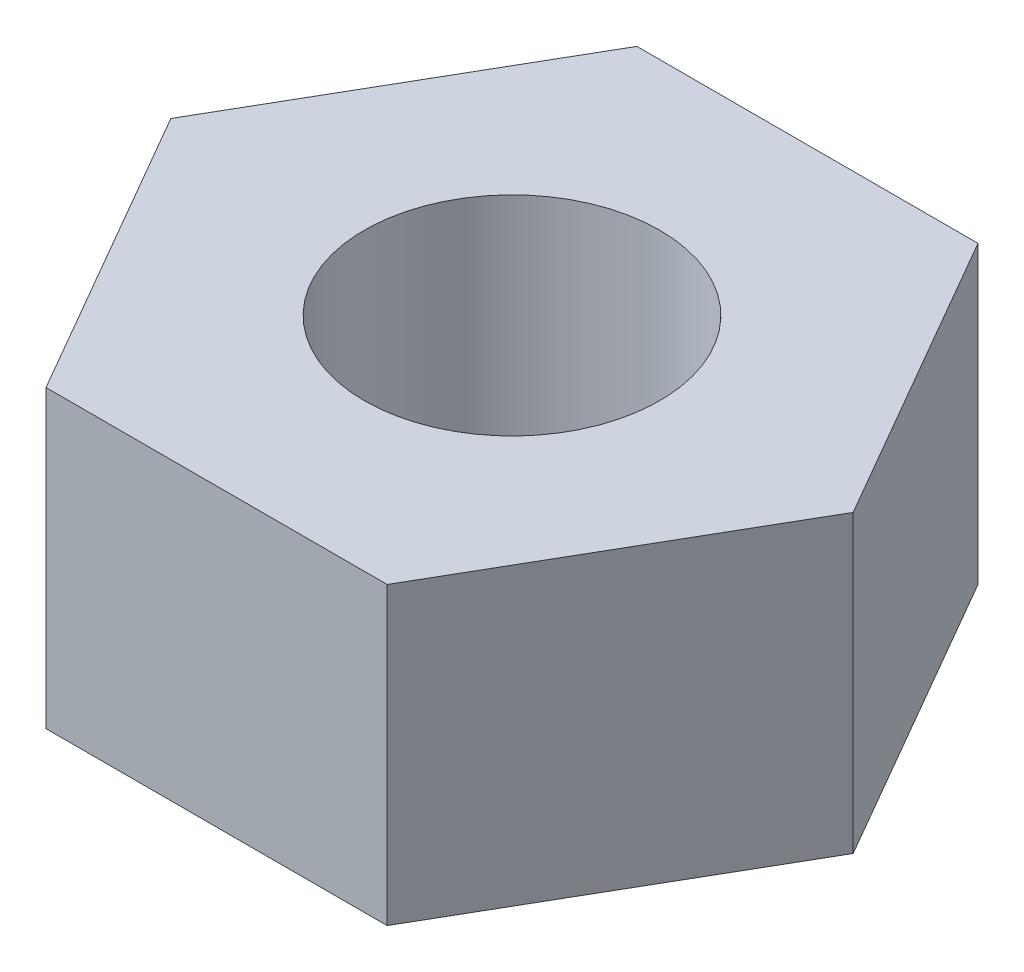
SolidWorks part; units mm, degrees
ref_plane "前视基准面" through (0, 0, 0) normal (0, 0, 1) x (1, 0, 0)
ref_plane "上视基准面" through (0, 0, 0) normal (0, 1, 0) x (1, 0, 0)
ref_plane "右视基准面" through (0, 0, 0) normal (1, 0, 0) x (0, 0, -1)
sketch "草图1" plane through (0, 0, 0) normal (0, 1, 0) x (1, 0, 0)
  line L1 (1.1547, 0) -> (0.5774, 1)
  line L2 (0.5774, 1) -> (-0.5774, 1)
  line L3 (-0.5774, 1) -> (-1.1547, 0)
  line L4 (-1.1547, 0) -> (-0.5774, -1)
  line L5 (-0.5774, -1) -> (0.5774, -1)
  line L6 (0.5774, -1) -> (1.1547, 0)
  circle A0 centre (0, 0) radius 1 construction
  circle A1 centre (0, 0) radius 0.5
  dimension "D1" = 1
  dimension "D2" = 2
extrude "凸台-拉伸1" add sketch "草图1" along normal blind 1
